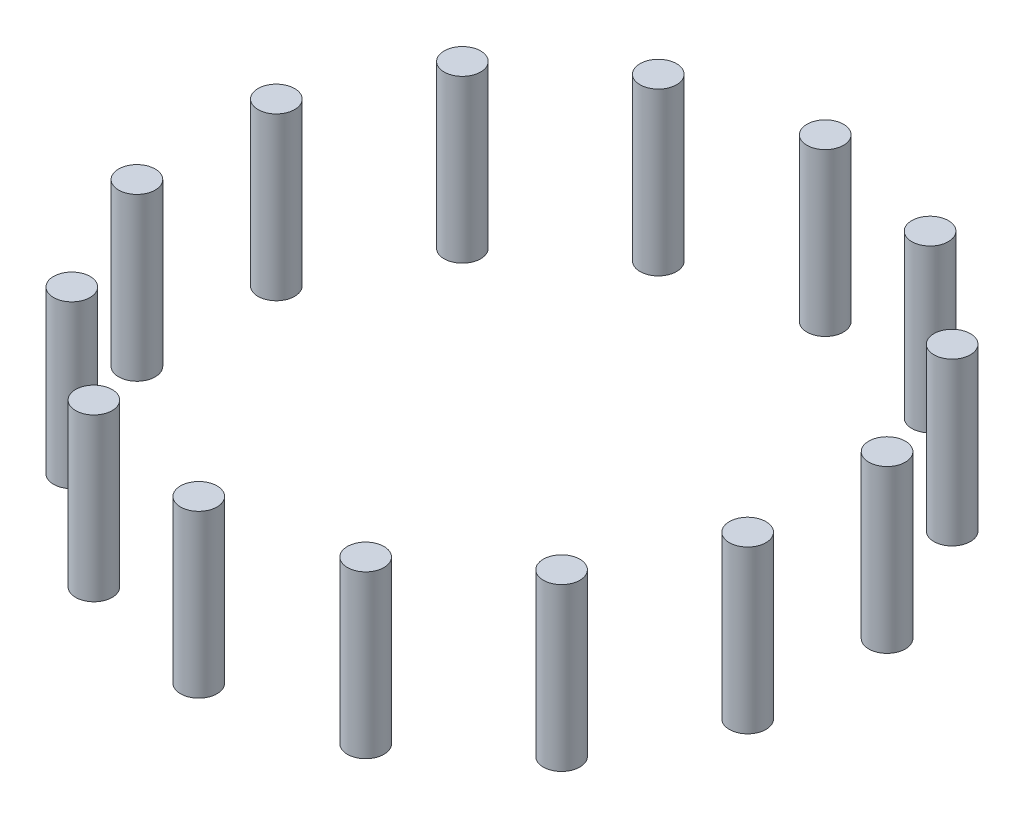
SolidWorks part; units mm, degrees
material "Nylon 6/10"
ref_plane "Front Plane" through (0, 0, 0) normal (0, 0, 1) x (1, 0, 0)
ref_plane "Top Plane" through (0, 0, 0) normal (0, 1, 0) x (1, 0, 0)
ref_plane "Right Plane" through (0, 0, 0) normal (1, 0, 0) x (0, 0, -1)
sketch "Sketch1" plane through (0, 0, 0) normal (0, 1, 0) x (-1, 0, 0)
  circle A0 centre (0, 6) radius 0.35
  circle A1 centre (2.6033, 5.4058) radius 0.35
  circle A2 centre (4.691, 3.7409) radius 0.35
  circle A3 centre (5.8496, 1.3351) radius 0.35
  circle A4 centre (5.8496, -1.3351) radius 0.35
  circle A5 centre (4.691, -3.7409) radius 0.35
  circle A6 centre (2.6033, -5.4058) radius 0.35
  circle A7 centre (0, -6) radius 0.35
  circle A8 centre (-2.6033, -5.4058) radius 0.35
  circle A9 centre (-4.691, -3.7409) radius 0.35
  circle A10 centre (-5.8496, -1.3351) radius 0.35
  circle A11 centre (-5.8496, 1.3351) radius 0.35
  circle A12 centre (-4.691, 3.7409) radius 0.35
  circle A13 centre (-2.6033, 5.4058) radius 0.35
  dimension "D1" = 14
extrude "Boss-Extrude1" add sketch "Sketch1" along normal blind 3.1
